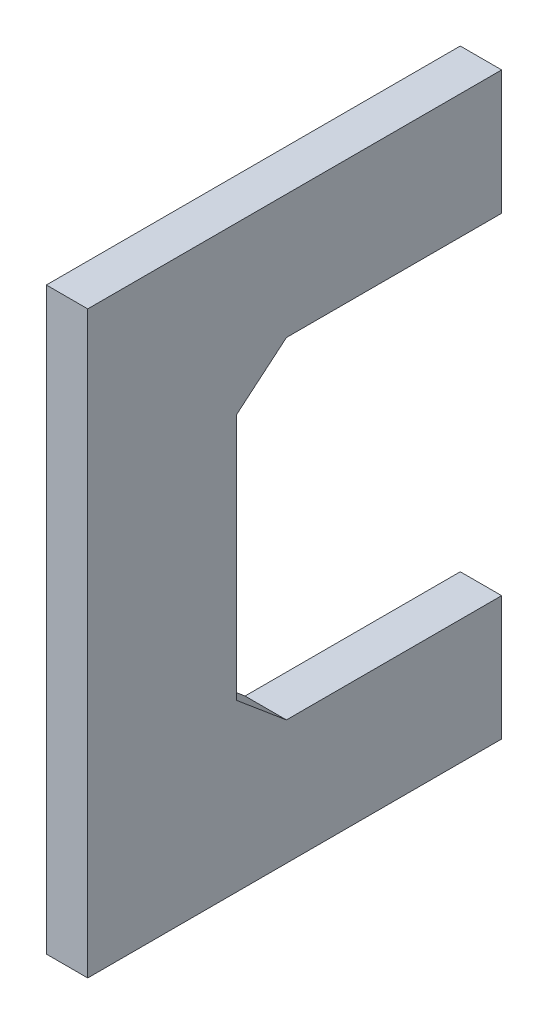
SolidWorks part; units mm, degrees
ref_plane "Front" through (0, 0, 0) normal (0, 0, 1) x (1, 0, 0)
ref_plane "Top" through (0, 0, 0) normal (0, 1, 0) x (1, 0, 0)
ref_plane "Right" through (0, 0, 0) normal (1, 0, 0) x (0, 0, -1)
sketch "Skizze1" plane through (0, 0, 0) normal (1, 0, 0) x (0, 0, -1)
  line L1 (0, 0) -> (50, 0)
  line L2 (0, 0) -> (0, 70)
  line L3 (0, 70) -> (50, 70)
  line L4 (50, 0) -> (50, 70)
  dimension "D1" = 50
  dimension "D2" = 70
extrude "Aufsatz-Linear austragen1" add sketch "Skizze1" along normal blind 5
sketch "Skizze2" plane through (5, 0, 0) normal (1, 0, 0) x (0, 0, -1)
  line L0 (50, 35) -> (18, 35) construction
  line L1 (50, 0) -> (50, 70) construction
  line L2 (18, 20.0346) -> (18, 49.9654)
  line L3 (18, 49.9654) -> (24, 55)
  line L4 (24, 55) -> (50, 55)
  line L5 (50, 55) -> (50, 15)
  line L6 (18, 20.0346) -> (24, 15)
  line L7 (24, 15) -> (50, 15)
  dimension "D1" = 26
  dimension "D2" = 40
  dimension "D3" = 140
  dimension "D4" = 32
extrude "Schnitt-Linear austragen1" cut sketch "Skizze2" against normal through all
